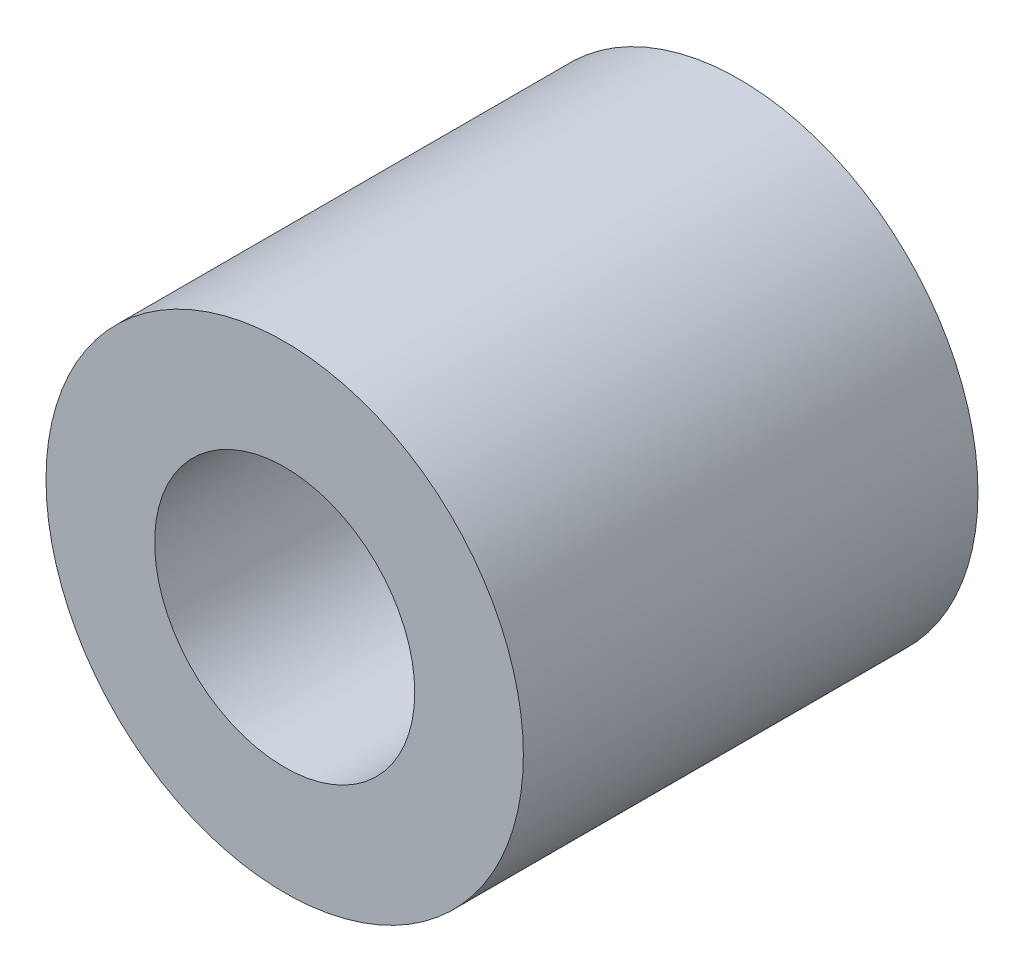
SolidWorks part; units mm, degrees
ref_plane "Front Plane" through (0, 0, 0) normal (0, 0, 1) x (1, 0, 0)
ref_plane "Top Plane" through (0, 0, 0) normal (0, 1, 0) x (1, 0, 0)
ref_plane "Right Plane" through (0, 0, 0) normal (1, 0, 0) x (0, 0, -1)
sketch "Sketch1" plane through (0, 0, 0) normal (0, 0, 1) x (1, 0, 0)
  circle A0 centre (0, 0) radius 9.45
  circle A1 centre (0, 0) radius 5.15
  dimension "D1" = 18.9
  dimension "D2" = 10.3
extrude "Boss-Extrude1" add sketch "Sketch1" along normal blind 18
